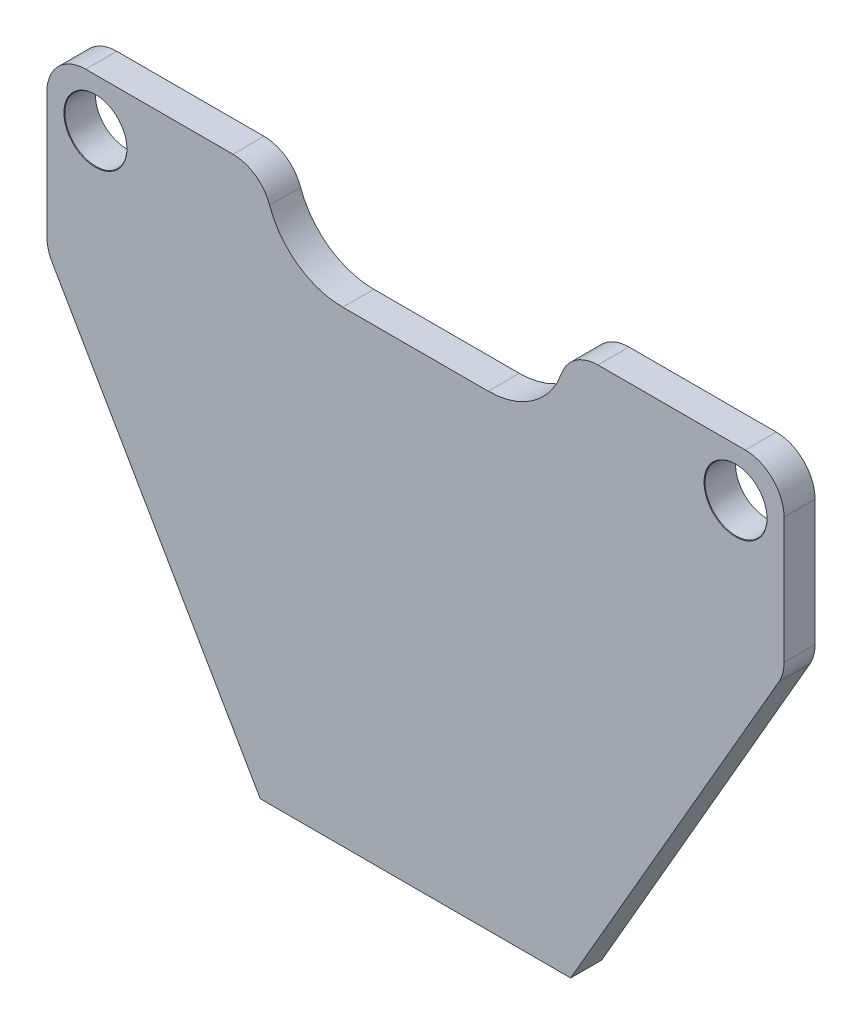
SolidWorks part; units mm, degrees
ref_plane "Front Plane" through (0, 0, 0) normal (0, 0, 1) x (1, 0, 0)
ref_plane "Top Plane" through (0, 0, 0) normal (0, 1, 0) x (1, 0, 0)
ref_plane "Right Plane" through (0, 0, 0) normal (1, 0, 0) x (0, 0, -1)
sketch "Sketch1" plane through (0, 0, 0) normal (0, 0, 1) x (1, 0, 0)
  line L0 (16.5, 44.5732) -> (-16.5, 44.5732) construction
  line L1 (0, 44.5732) -> (0, 25) construction
  line L2 (8, 19) -> (-8, 19)
  line L3 (-8, 19) -> (-19, 38.0526)
  line L4 (-19, 38.0526) -> (-19, 47.0732) construction
  line L5 (-19, 47.0732) -> (19, 47.0732) construction
  line L7 (-17, 47.0732) -> (17, 47.0732) construction
  line L8 (8, 19) -> (19, 38.0526)
  line L9 (19, 38.0526) -> (19, 47.0732) construction
  line L10 (-19, 38.0526) -> (-19, 47.0732)
  line L12 (19, 47.0732) -> (19, 38.0526)
  line L13 (-3.75, 47.0732) -> (3.75, 47.0732) construction
  line L14 (-3.75, 51.0732) -> (3.75, 51.0732) construction
  line L15 (-3.75, 43.0732) -> (3.75, 43.0732) construction
  line L16 (-3.75, 43.0732) -> (3.75, 43.0732)
  line L17 (-19, 47.0732) -> (-7.75, 47.0732)
  line L18 (7.75, 47.0732) -> (19, 47.0732)
  line L19 (-19, 0) -> (-19, 45.0732) construction
  arc A4 (-3.75, 51.0732) -> (-3.75, 43.0732) centre (-3.75, 47.0732) ccw construction
  arc A5 (3.75, 43.0732) -> (3.75, 51.0732) centre (3.75, 47.0732) ccw construction
  arc A6 (-7.75, 47.0732) -> (-3.75, 43.0732) centre (-3.75, 47.0732) ccw
  arc A7 (3.75, 43.0732) -> (7.75, 47.0732) centre (3.75, 47.0732) ccw
  point P12 (0, 0)
  point P16 (17, 38.2069)
  point P17 (0, 0)
  point P18 (-19, 32)
  point P20 (0, 19)
  point P22 (0, 47.0732)
  point P33 (0, 47.0732)
  point P45 (7.75, 47.0732)
  point P48 (-7.75, 47.0732)
  dimension "D4" = 4
  dimension "D6" = 7.5
  dimension "D1" = 150
  dimension "D2" = 8
  dimension "D3" = 6
extrude "Boss-Extrude1" add sketch "Sketch1" along normal blind 1.6
hole_wizard "M3 Clearance Hole1" positions "Sketch2" profile "Sketch3" hole size "M3" standard "ANSI Metric" end condition through all
sketch "Sketch2" plane through (0, 0, 1.6) normal (0, 0, 1) x (1, 0, 0)
  point P18 (16.5, 44.5732)
  point P21 (-16.5, 44.5732)
  point P25 (0, 0)
  point P26 (0, 0)
sketch "Sketch3" plane through (16.5, 44.5732, 1.6) normal (1, 0, 0) x (0, -1, 0)
  line L0 (0, 0) -> (0, 1.6)
  line L1 (0, 1.6) -> (1.6, 1.6)
  line L2 (1.6, 1.6) -> (1.6, 0.025)
  line L3 (1.6, 0.025) -> (1.625, 0)
  line L5 (1.625, 0) -> (0, 0)
  line L6 (-1.6, 0.025) -> (-1.625, 0) construction
  line L11 (0, -6.35) -> (0, 107.95) construction
  dimension "Thru Hole Dia." = 3.2
  dimension "Thru Hole Depth" = 1.6
  dimension "Near C'Sink Dia." = 3.25
  dimension "Near C'Sink Angle" = 90
fillet "Fillet1" radius 2 6 edges at (19, 38.0526, 0.8) (-19, 38.0526, 0.8) (-19, 47.0732, 0.8) (-7.75, 47.0732, 0.8) (7.75, 47.0732, 0.8) (19, 47.0732, 0.8)
